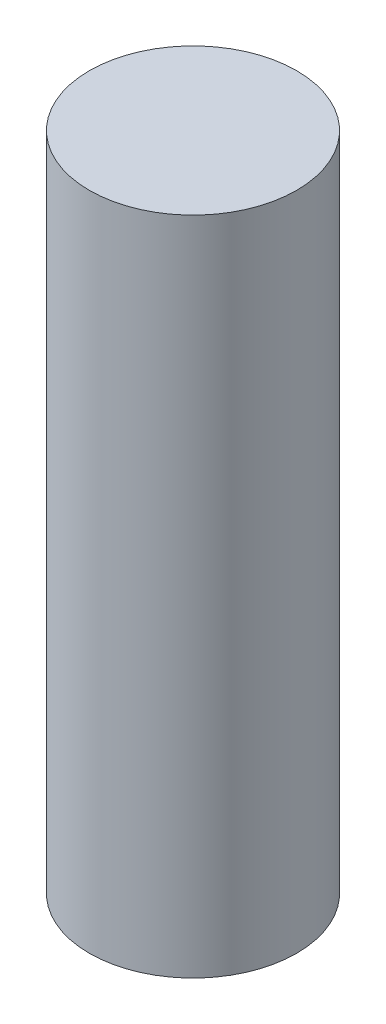
SolidWorks part; units mm, degrees
ref_plane "前视基准面" through (0, 0, 0) normal (0, 0, 1) x (1, 0, 0)
ref_plane "上视基准面" through (0, 0, 0) normal (0, 1, 0) x (1, 0, 0)
ref_plane "右视基准面" through (0, 0, 0) normal (1, 0, 0) x (0, 0, -1)
other "Configuration Table"
sketch "草图1" plane through (0, 0, 0) normal (0, 0, 1) x (1, 0, 0)
  line L0 (0, 0) -> (4, 0)
  line L1 (4, 0) -> (4, 25.5)
  line L2 (4, 25.5) -> (0, 25.5)
  line L3 (0, 25.5) -> (0, 0)
  line L4 (0, 0) -> (0, 25.5) construction
  dimension "radius" = 4
  dimension "height" = 25.5
revolve "Revolve" add sketch "草图1" angle 360 about L4
